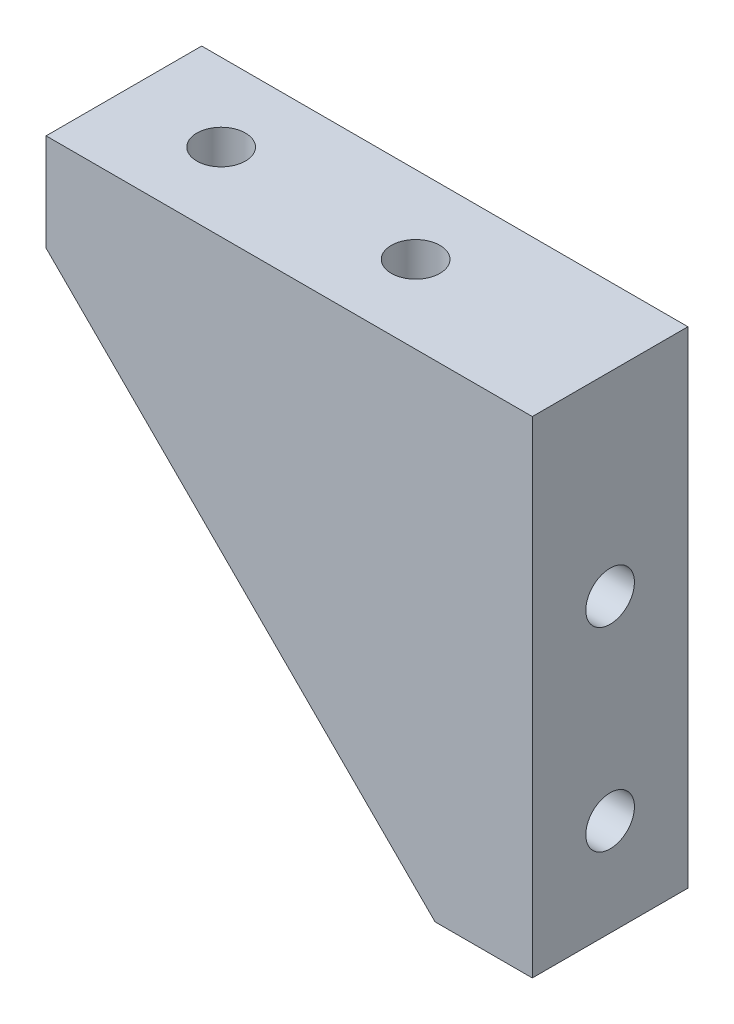
SolidWorks part; units mm, degrees
material "6061 Сплав"
ref_plane "Front" through (0, 0, 0) normal (0, 0, 1) x (1, 0, 0)
ref_plane "Top" through (0, 0, 0) normal (0, 1, 0) x (1, 0, 0)
ref_plane "Right" through (0, 0, 0) normal (1, 0, 0) x (0, 0, -1)
sketch "Эскиз1" plane through (0, 0, 0) normal (0, 0, 1) x (1, 0, 0)
  line L1 (-12.5, 12.5) -> (12.5, 12.5)
  line L2 (-12.5, 12.5) -> (-12.5, -12.5)
  line L3 (-12.5, -12.5) -> (12.5, -12.5)
  line L4 (12.5, 12.5) -> (12.5, -12.5)
  line L5 (-12.5, 12.5) -> (12.5, -12.5) construction
  line L6 (-12.5, -12.5) -> (12.5, 12.5) construction
  point P0 (0, 0)
  dimension "D1" = 25
  dimension "D2" = 25
extrude "Бобышка-Вытянуть1" add sketch "Эскиз1" along normal blind 8
sketch "Эскиз2" plane through (0, 12.5, 0) normal (0, 1, 0) x (1, 0, 0)
  line L1 (12.5, -8) -> (-12.5, -8) construction
  line L2 (12.5, -8) -> (12.5, 0) construction
  circle A0 centre (-7.5, -4) radius 1.25
  circle A1 centre (2.5, -4) radius 1.25
  dimension "D1" = 10
  dimension "D2" = 10
  dimension "D3" = 4
  dimension "D4" = 4
extrude "Вырез-Вытянуть1" cut sketch "Эскиз2" against normal blind 50
sketch "Эскиз3" plane through (12.5, 0, 0) normal (1, 0, 0) x (0, 0, -1)
  line L1 (-8, -12.5) -> (-8, 12.5) construction
  line L2 (-8, 12.5) -> (0, 12.5) construction
  circle A0 centre (-4, 2.5) radius 1.25
  circle A1 centre (-4, -7.5) radius 1.25
  dimension "D1" = 10
  dimension "D2" = 4
  dimension "D3" = 4
  dimension "D4" = 10
extrude "Вырез-Вытянуть2" cut sketch "Эскиз3" against normal blind 50
sketch "Эскиз4" plane through (0, 0, 0) normal (0, 0, -1) x (-1, 0, 0)
  line L0 (12.5, 7.5) -> (-7.5, -12.5)
  line L1 (12.5, 12.5) -> (12.5, -12.5) construction
  line L2 (12.5, -12.5) -> (-12.5, -12.5) construction
  line L3 (-12.5, -12.5) -> (-12.5, 12.5) construction
  line L4 (12.5, 7.5) -> (12.5, -12.5)
  line L5 (12.5, -12.5) -> (-7.5, -12.5)
  dimension "D1" = 5
  dimension "D2" = 5
extrude "Вырез-Вытянуть4" cut sketch "Эскиз4" against normal blind 10
